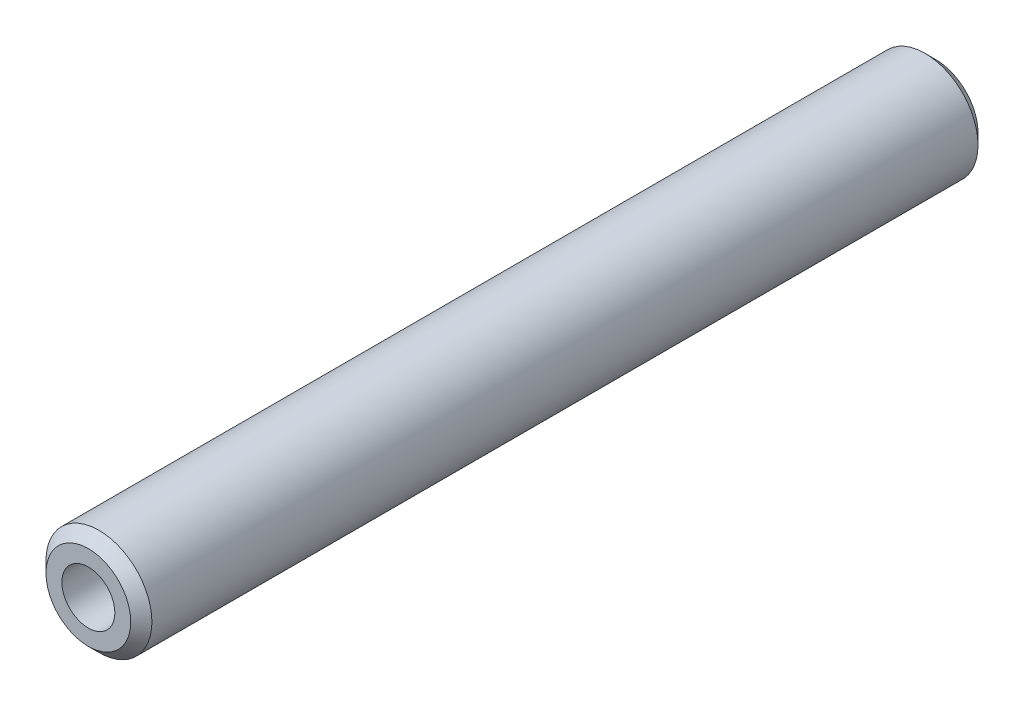
SolidWorks part; units mm, degrees
ref_plane "Front Plane" through (0, 0, 0) normal (0, 0, 1) x (1, 0, 0)
ref_plane "Top Plane" through (0, 0, 0) normal (0, 1, 0) x (1, 0, 0)
ref_plane "Right Plane" through (0, 0, 0) normal (1, 0, 0) x (0, 0, -1)
sketch "Sketch1" plane through (0, 0, 0) normal (0, 0, 1) x (1, 0, 0)
  circle A0 centre (0, 0) radius 2.5
  dimension "D1" = 5
extrude "Boss-Extrude1" add sketch "Sketch1" along normal mid plane 40
hole_wizard "M3x0.5 Tapped Hole1" positions "Sketch2" profile "Sketch3" tap size "M3x0.5" standard "ANSI Metric" end condition through all
sketch "Sketch2" plane through (0, 0, 20) normal (0, 0, 1) x (1, 0, 0)
  point P0 (0, 0)
sketch "Sketch3" plane through (0, 0, 20) normal (1, 0, 0) x (0, -1, 0)
  line L0 (0, 0) -> (0, 40)
  line L1 (0, 40) -> (1.25, 40)
  line L2 (1.25, 40) -> (1.25, 0)
  line L5 (1.25, 0) -> (0, 0)
  line L11 (0, -6.35) -> (0, 107.95) construction
  dimension "Thru Tap Drill Dia." = 2.5
  dimension "Thru Tap Drill Depth" = 40
cosmetic thread "Hole Thread1" parameters "D2"=3
chamfer "Chamfer1" distance 0.5 angle 45 2 edges at (2.5, 0, -20) (2.5, 0, 20)
